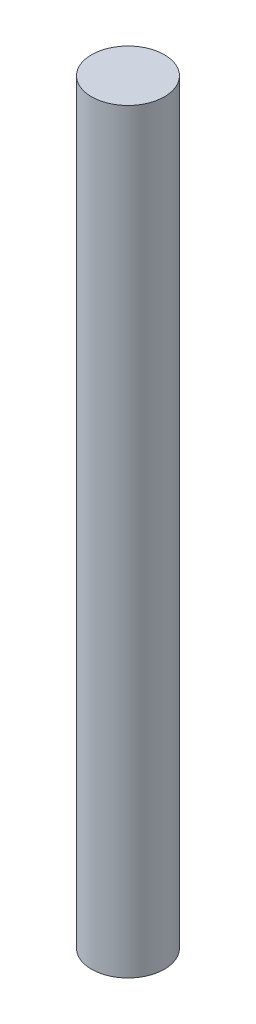
SolidWorks part; units mm, degrees
ref_plane "Front Plane" through (0, 0, 0) normal (0, 0, 1) x (1, 0, 0)
ref_plane "Top Plane" through (0, 0, 0) normal (0, 1, 0) x (1, 0, 0)
ref_plane "Right Plane" through (0, 0, 0) normal (1, 0, 0) x (0, 0, -1)
sketch "Sketch1" plane through (0, 0, 0) normal (0, 0, 1) x (1, 0, 0)
  line L0 (0, 0) -> (0, 88.9) construction
  line L1 (-4.2862, 0) -> (-4.2862, 88.9)
  line L6 (-4.2862, 88.9) -> (0, 88.9)
  line L7 (-4.2862, 0) -> (0, 0)
  line L8 (0, 88.9) -> (0, 0)
  dimension "D1" = 88.9
  dimension "D3" = 8.5725
revolve "Revolve1" add sketch "Sketch1" angle 360 about L8
